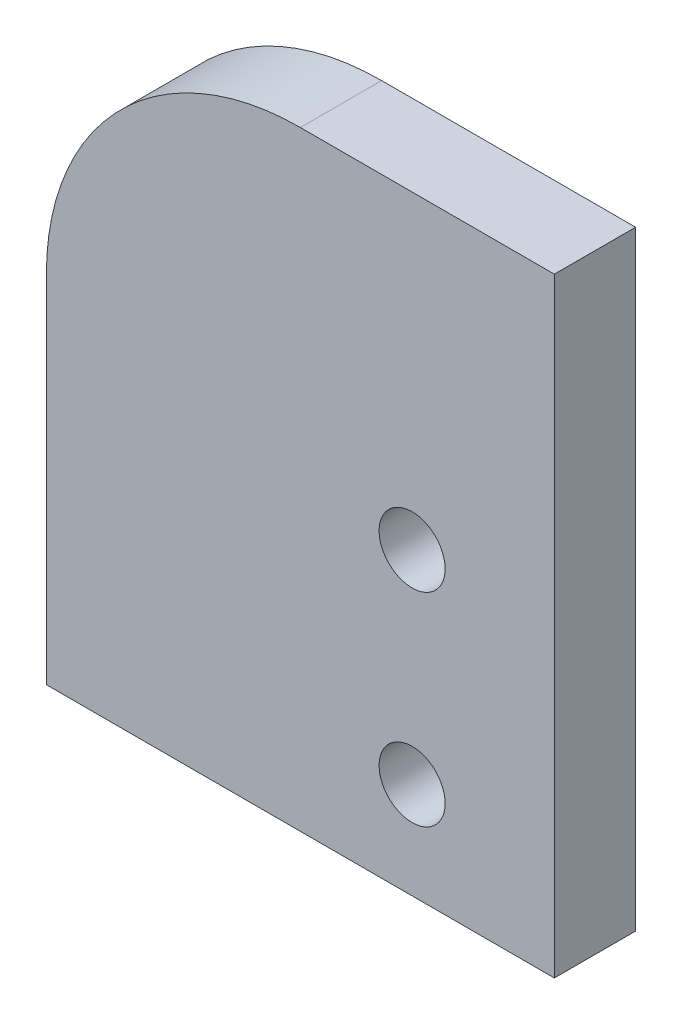
SolidWorks part; units mm, degrees
ref_plane "Ebene vorne" through (0, 0, 0) normal (0, 0, 1) x (1, 0, 0)
ref_plane "Ebene oben" through (0, 0, 0) normal (0, 1, 0) x (1, 0, 0)
ref_plane "Ebene rechts" through (0, 0, 0) normal (1, 0, 0) x (0, 0, -1)
sketch "Sketch1" plane through (0, 0, 0) normal (0, 0, 1) x (1, 0, 0)
  line L0 (0, 20) -> (0, 30)
  line L1 (0, 0) -> (-25, 0)
  line L2 (0, 0) -> (0, 20)
  line L3 (-12.5, 30) -> (0, 30)
  line L4 (-25, 0) -> (-25, 17.5)
  arc A0 (-12.5, 30) -> (-25, 17.5) centre (-12.5, 17.5) ccw
  dimension "D1" = 20
  dimension "D2" = 25
  dimension "D3" = 10
extrude "Boss-Extrude1" add sketch "Sketch1" along normal blind 4
sketch "Sketch2" plane through (0, 0, 4) normal (0, 0, 1) x (1, 0, 0)
  line L0 (0, 0) -> (0, 30) construction
  line L1 (-25, 0) -> (0, 0) construction
  circle A0 centre (-7, 14.75) radius 1.625
  circle A1 centre (-7, 4.75) radius 1.625
  dimension "D1" = 3.25
  dimension "D2" = 7
  dimension "D3" = 10
  dimension "D4" = 4.75
extrude "Cut-Extrude1" cut sketch "Sketch2" against normal through all
